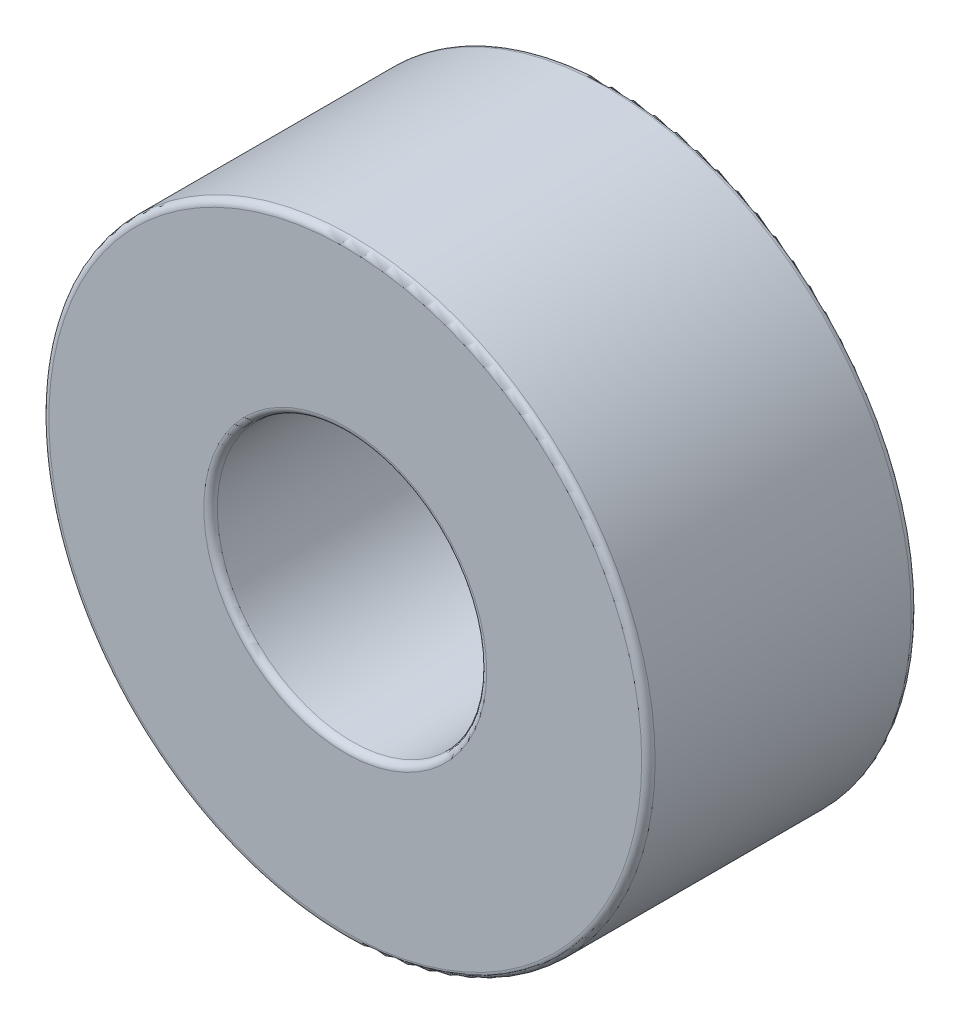
SolidWorks part; units mm, degrees
material "Nylon 101"
ref_plane "Front Plane" through (0, 0, 0) normal (0, 0, 1) x (1, 0, 0)
ref_plane "Top Plane" through (0, 0, 0) normal (0, 1, 0) x (1, 0, 0)
ref_plane "Right Plane" through (0, 0, 0) normal (1, 0, 0) x (0, 0, -1)
sketch "Sketch1" plane through (0, 0, 0) normal (0, 0, 1) x (1, 0, 0)
  circle A0 centre (0, 0) radius 4.5
  circle A1 centre (0, 0) radius 2
  dimension "D1" = 9
  dimension "D2" = 4
extrude "Boss-Extrude1" add sketch "Sketch1" along normal blind 4
fillet "Fillet1" radius 0.1 4 edges at (2, 0, 0) (4.5, 0, 0) (2, 0, 4) (4.5, 0, 4)
